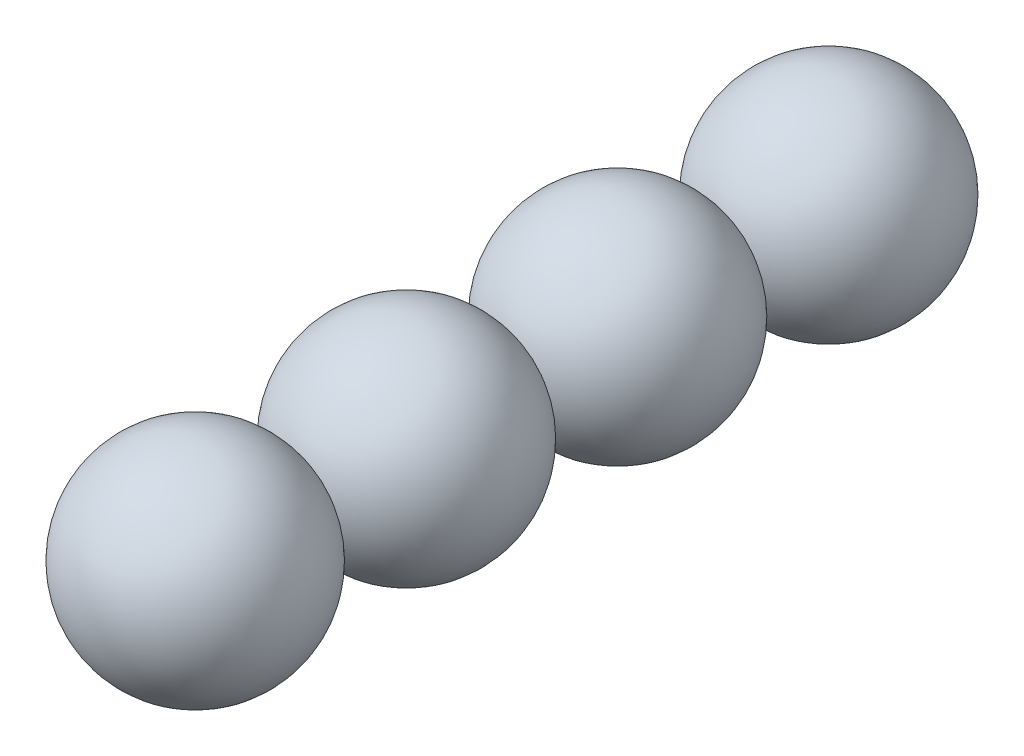
SolidWorks part; units mm, degrees
ref_plane "前基準面" through (0, 0, 0) normal (0, 0, 1) x (1, 0, 0)
ref_plane "上基準面" through (0, 0, 0) normal (0, 1, 0) x (1, 0, 0)
ref_plane "右基準面" through (0, 0, 0) normal (1, 0, 0) x (0, 0, -1)
sketch "草圖1" plane through (0, 0, 0) normal (0, 0, 1) x (1, 0, 0)
  line L0 (0, 30) -> (0, -30)
  arc A0 (0, -30) -> (0, 30) centre (0, 0) ccw
  dimension "D1" = 60
revolve "旋轉1" add sketch "草圖1" angle 360 about L0
pattern_linear "直線複製排列1" count 4 spacing 60 along (0, 0, 1) of "旋轉1"
